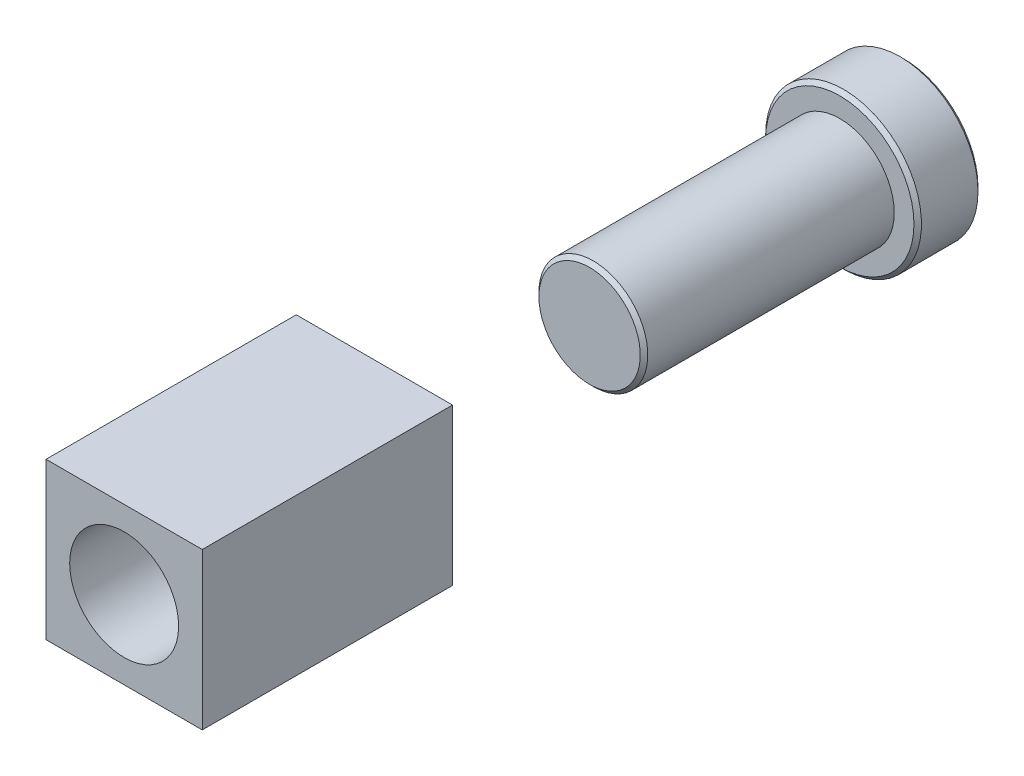
SolidWorks part; units mm, degrees
ref_plane "Front Plane" through (0, 0, 0) normal (0, 0, 1) x (1, 0, 0)
ref_plane "Top Plane" through (0, 0, 0) normal (0, 1, 0) x (1, 0, 0)
ref_plane "Right Plane" through (0, 0, 0) normal (1, 0, 0) x (0, 0, -1)
sketch "Sketch1" plane through (0, 0, 0) normal (0, 0, 1) x (1, 0, 0)
  circle A0 centre (0, 0) radius 15.8115
  dimension "D1" = 31.623
extrude "Boss-Extrude1" add sketch "Sketch1" along normal blind 12.9988
sketch "Sketch2" plane through (0, 0, 12.9988) normal (0, 0, 1) x (1, 0, 0)
  circle A0 centre (0, 0) radius 11.049
  dimension "D1" = 22.098
extrude "Boss-Extrude2" add sketch "Sketch2" along normal blind 50.8
ref_plane "Plane1" through (0, 0, 107.4833) normal (0, 0, 1) x (1, 0, 0)
sketch "Sketch3" plane through (0, 0, 107.4833) normal (0, 0, 1) x (1, 0, 0)
  line L0 (15.8613, -15.8613) -> (-15.8613, 15.8613) construction
  line L1 (-15.8613, 15.8613) -> (15.8613, 15.8613)
  line L2 (-15.8613, 15.8613) -> (-15.8613, -15.8613)
  line L3 (-15.8613, -15.8613) -> (15.8613, -15.8613)
  line L4 (15.8613, 15.8613) -> (15.8613, -15.8613)
extrude "Boss-Extrude3" add sketch "Sketch3" along normal blind 50.8 separate body
sketch "Sketch4" plane through (0, 0, 107.4833) normal (0, 0, -1) x (-1, 0, 0)
  circle A0 centre (0, 0) radius 11.0553
  dimension "D1" = 22.1107
extrude "Cut-Extrude1" cut sketch "Sketch4" against normal through all
chamfer "Chamfer1" distance 0.762 angle 45 3 edges at (15.8115, 0, 0) (15.8115, 0, 12.9988) (11.049, 0, 63.7988)
equation "\"Pin Shaft Diameter\"= .87in"
equation "\"Base Length\"= \"D1@Boss-Extrude3\""
equation "\"D1@Sketch1\"= \"Pin Shaft Diameter\" + .375'The pin head diameter is .375 inches bigger than the pin shaft diamter."
equation "\"D1@Boss-Extrude1\"=\"Pin Shaft Diameter\" / 1.7"
equation "\"D1@Boss-Extrude2\"= \"Base Length\""
equation "\"D1@Sketch4\"= \"Pin Shaft Diameter\" + .0005"
equation "\"D1@Sketch2\"= \"Pin Shaft Diameter\""
equation "\"Chamfer1\"= IIF ( \"Pin Shaft Diameter\" < 1mm , \"suppressed\" , \"unsuppressed\" )"
